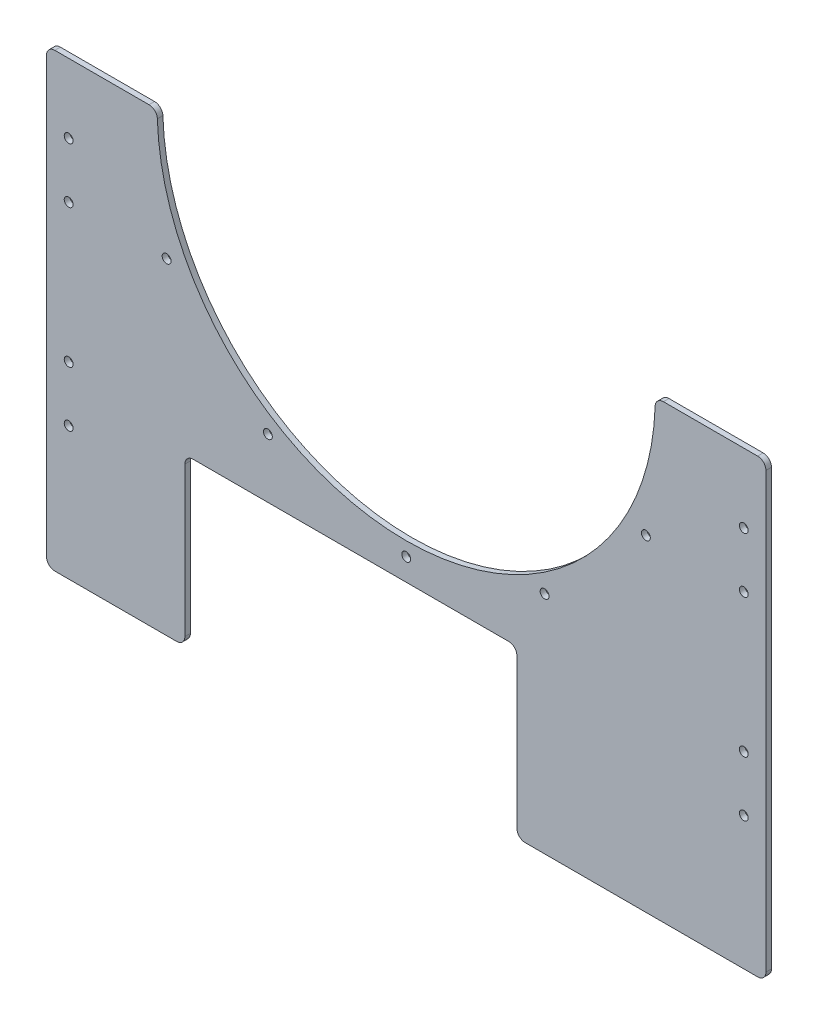
SolidWorks part; units mm, degrees
material "Thornel Mat VMA"
ref_plane "前视基准面" through (0, 0, 0) normal (0, 0, 1) x (1, 0, 0)
ref_plane "上视基准面" through (0, 0, 0) normal (0, 1, 0) x (1, 0, 0)
ref_plane "右视基准面" through (0, 0, 0) normal (1, 0, 0) x (0, 0, -1)
other "Configuration Table"
sketch "草图1" plane through (0, 0, 0) normal (0, 0, 1) x (1, 0, 0)
  line L1 (130, -81.5) -> (-130, -81.5)
  line L2 (130, -81.5) -> (130, 81.5)
  line L3 (130, 81.5) -> (-130, 81.5)
  line L4 (-130, -81.5) -> (-130, 81.5)
  line L5 (130, -81.5) -> (-130, 81.5) construction
  line L6 (130, 81.5) -> (-130, -81.5) construction
  point P0 (0, 0)
  dimension "D1" = 163
  dimension "D2" = 260
extrude "凸台-拉伸1" add sketch "草图1" along normal blind 2
sketch "草图2" plane through (0, 0, 2) normal (0, 0, 1) x (1, 0, 0)
  line L0 (-122, 81.5) -> (-122, -81.5) construction
  line L1 (130, 81.5) -> (-130, 81.5) construction
  line L2 (-130, -81.5) -> (130, -81.5) construction
  line L3 (-130, 81.5) -> (-130, -81.5) construction
  line L4 (0, 81.5) -> (0, -81.5) construction
  circle A0 centre (-122, -33.5) radius 1.6
  circle A1 centre (-122, -13.5) radius 1.6
  circle A2 centre (-122, 36.5) radius 1.6
  circle A3 centre (-122, 56.5) radius 1.6
  circle A4 centre (122, 56.5) radius 1.6
  circle A5 centre (122, 36.5) radius 1.6
  circle A6 centre (122, -13.5) radius 1.6
  circle A7 centre (122, -33.5) radius 1.6
  dimension "D1" = 3.2
  dimension "D2" = 20
  dimension "D3" = 20
  dimension "D4" = 50
  dimension "D5" = 48
  dimension "D6" = 8
extrude "切除-拉伸1" cut sketch "草图2" against normal blind 2
fillet "圆角1" radius 3 4 edges at (130, 81.5, 1) (130, -81.5, 1) (-130, -81.5, 1) (-130, 81.5, 1)
sketch "草图3" plane through (0, 0, 2) normal (0, 0, 1) x (1, 0, 0)
  line L0 (-127, -81.5) -> (127, -81.5) construction
  line L1 (0, 86.5) -> (0, -13.5) construction
  circle A0 centre (0, 81.5) radius 90
  circle A1 centre (0, 81.5) radius 95 construction
  circle A2 centre (0, -13.5) radius 1.6
  circle A4 centre (-50, -0.1025) radius 1.6
  circle A5 centre (-86.6025, 36.5) radius 1.6
  circle A13 centre (86.6025, 36.5) radius 1.6
  circle A14 centre (50, -0.1025) radius 1.6
  circle A15 centre (-100, 86.5) radius 1.6 [skipped]
  circle A16 centre (-86.6025, 136.5) radius 1.6 [skipped]
  circle A17 centre (-50, 173.1025) radius 1.6 [skipped]
  circle A18 centre (50, 173.1025) radius 1.6 [skipped]
  circle A19 centre (0, 186.5) radius 1.6 [skipped]
  circle A20 centre (86.6025, 136.5) radius 1.6 [skipped]
  circle A21 centre (100, 86.5) radius 1.6 [skipped]
  dimension "D2" = 180
  dimension "D3" = 190
  dimension "D4" = 3.2
  dimension "D1" = 163
  dimension "D6" = 100
  dimension "D5" = 12
extrude "切除-拉伸2" cut sketch "草图3" against normal blind 2
sketch "草图4" plane through (0, 0, 2) normal (0, 0, 1) x (1, 0, 0)
  line L0 (-127, -81.5) -> (127, -81.5) construction
  line L1 (-80, -81.5) -> (40, -81.5)
  line L2 (-80, -81.5) -> (-80, -21.5)
  line L3 (-80, -21.5) -> (40, -21.5)
  line L4 (40, -81.5) -> (40, -21.5)
  line L5 (-130, 78.5) -> (-130, -78.5) construction
  dimension "D1" = 50
  dimension "D2" = 120
  dimension "D3" = 60
extrude "切除-拉伸3" cut sketch "草图4" against normal blind 2
fillet "圆角2" radius 3 6 edges at (-80, -81.5, 1) (-90, 81.5, 1) (90, 81.5, 1) (40, -81.5, 1) (40, -21.5, 1) (-80, -21.5, 1)
